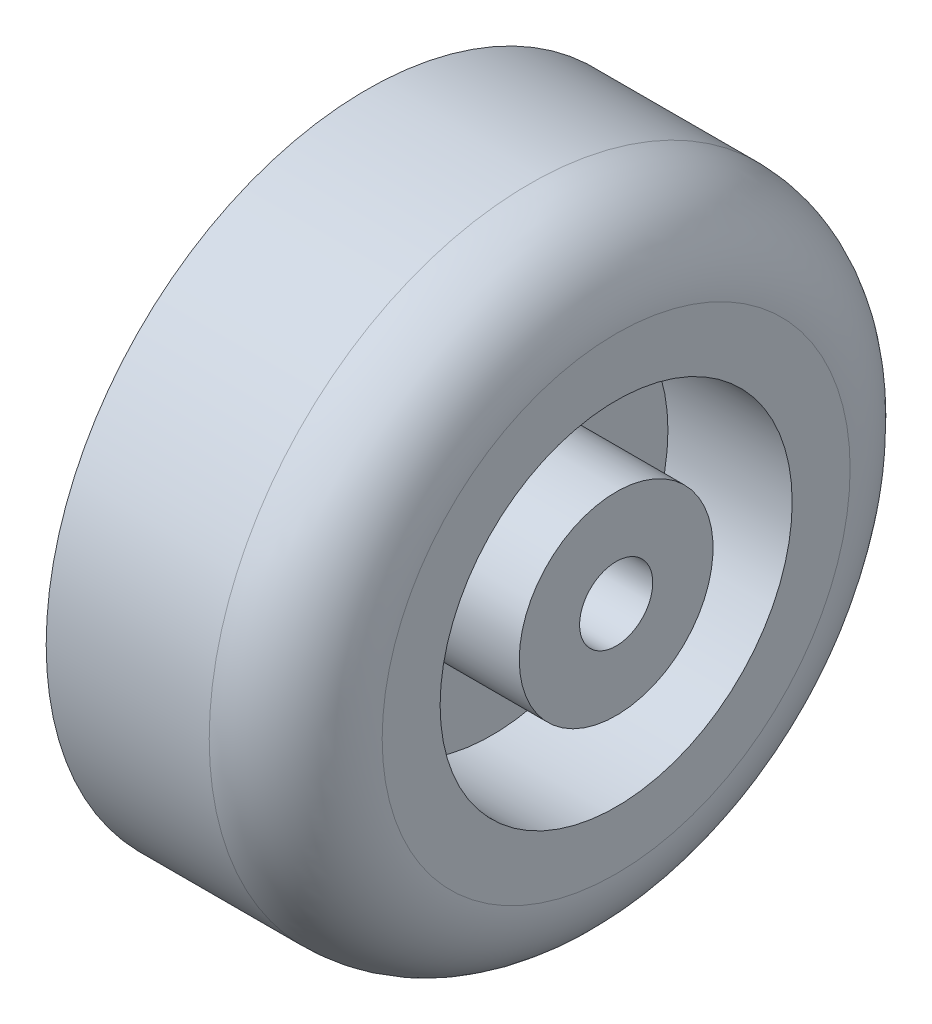
SolidWorks part; units mm, degrees
ref_plane "Front Plane" through (0, 0, 0) normal (0, 0, 1) x (1, 0, 0)
ref_plane "Top Plane" through (0, 0, 0) normal (0, 1, 0) x (1, 0, 0)
ref_plane "Right Plane" through (0, 0, 0) normal (1, 0, 0) x (0, 0, -1)
sketch "Sketch1" plane through (0, 0, 0) normal (0, 0, 1) x (1, 0, 0)
  line L0 (0, 333.4912) -> (259.6589, 333.4912)
  line L1 (259.6589, 333.4912) -> (259.6589, 183.19)
  line L2 (259.6589, 183.19) -> (130.3668, 183.19)
  line L3 (130.3668, 183.19) -> (130.3668, 100.8426)
  line L4 (130.3668, 100.8426) -> (259.6589, 100.8426)
  line L5 (259.6589, 100.8426) -> (259.6589, 38.0759)
  line L6 (259.6589, 38.0759) -> (0, 38.0759)
  line L7 (0, 38.0759) -> (0, 333.4912)
  line L8 (0, 38.0759) -> (0, -8.8886) construction
  line L9 (0, 0) -> (37.3285, 0) construction
revolve "Revolve1" add sketch "Sketch1" angle 360 about L9
fillet "Fillet1" radius 90 1 edges at (259.6589, 0, 333.4912)
